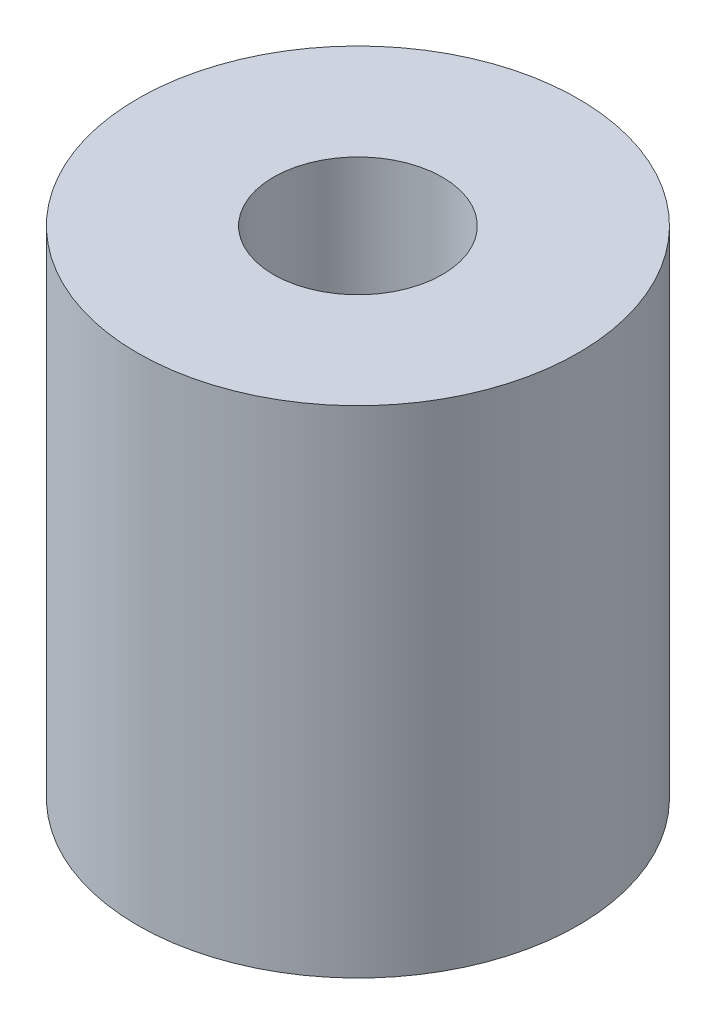
SolidWorks part; units mm, degrees
ref_plane "Płaszczyzna przednia" through (0, 0, 0) normal (0, 0, 1) x (1, 0, 0)
ref_plane "Płaszczyzna górna" through (0, 0, 0) normal (0, 1, 0) x (1, 0, 0)
ref_plane "Płaszczyzna prawa" through (0, 0, 0) normal (1, 0, 0) x (0, 0, -1)
sketch "Sketch1" plane through (0, 0, 0) normal (0, 1, 0) x (1, 0, 0)
  circle A0 centre (0, 0) radius 6
  circle A1 centre (0, 0) radius 2.3
  dimension "D1" = 12
  dimension "D2" = 4.6
extrude "Boss-Extrude1" add sketch "Sketch1" along normal blind 13.5
